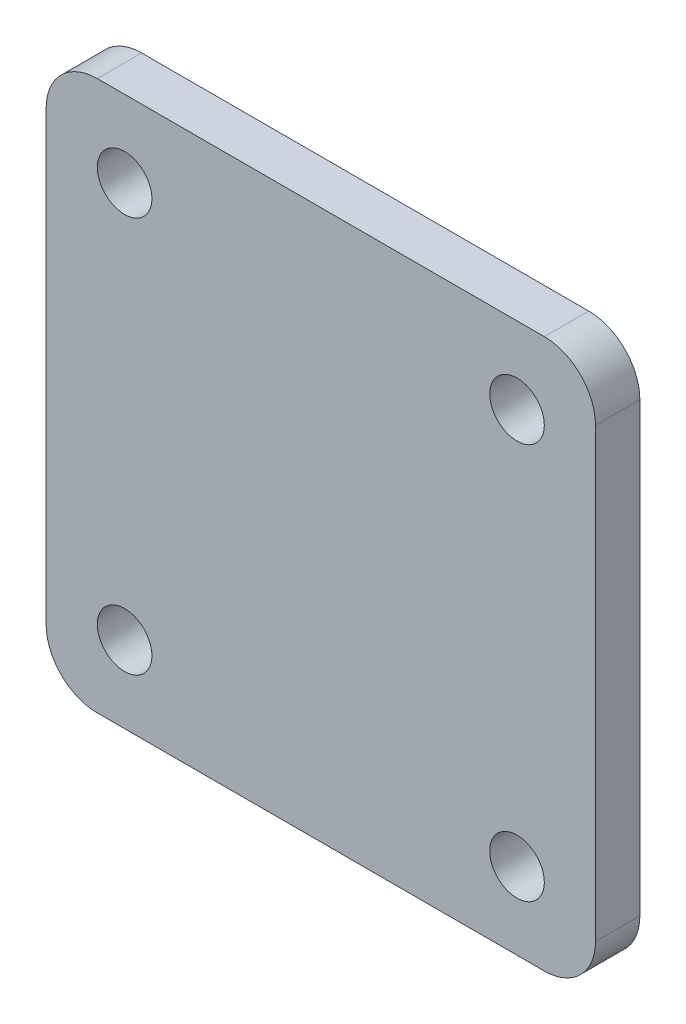
SolidWorks part; units mm, degrees
ref_plane "Front Plane" through (0, 0, 0) normal (0, 0, 1) x (1, 0, 0)
ref_plane "Top Plane" through (0, 0, 0) normal (0, 1, 0) x (1, 0, 0)
ref_plane "Right Plane" through (0, 0, 0) normal (1, 0, 0) x (0, 0, -1)
sketch "Sketch1" plane through (0, 0, 0) normal (0, 0, 1) x (1, 0, 0)
  line L0 (-11.5, 11.6) -> (11.5, 11.6) construction
  line L6 (-16.1, -16.1) -> (16.1, -16.1)
  line L7 (-11.5, 11.6) -> (-11.5, -11.6) construction
  line L8 (-11.5, -11.6) -> (11.5, -11.6) construction
  line L9 (11.5, 11.6) -> (11.5, -11.6) construction
  line L10 (-11.5, 11.6) -> (11.5, -11.6) construction
  line L11 (-11.5, -11.6) -> (11.5, 11.6) construction
  line L12 (-16.1, -16.1) -> (-16.1, 16.1)
  line L13 (-16.1, 16.1) -> (16.1, 16.1)
  line L14 (16.1, -16.1) -> (16.1, 16.1)
  line L15 (-16.1, -16.1) -> (16.1, 16.1) construction
  line L16 (-16.1, 16.1) -> (16.1, -16.1) construction
  circle A4 centre (-11.5, -11.6) radius 1.6
  circle A5 centre (-11.5, 11.6) radius 1.6
  circle A6 centre (11.5, 11.6) radius 1.6
  circle A7 centre (11.5, -11.6) radius 1.6
  point P0 (0, 0)
  point P7 (13.1, -11.6)
  point P25 (0, 0)
  dimension "D3" = 3.2
  dimension "D1" = 3
  dimension "D4" = 23
  dimension "D5" = 23.2
extrude "Boss-Extrude1" add sketch "Sketch1" along normal blind 2.6
fillet "Fillet1" radius 3 4 edges at (-16.1, -16.1, 1.3) (16.1, -16.1, 1.3) (16.1, 16.1, 1.3) (-16.1, 16.1, 1.3)
